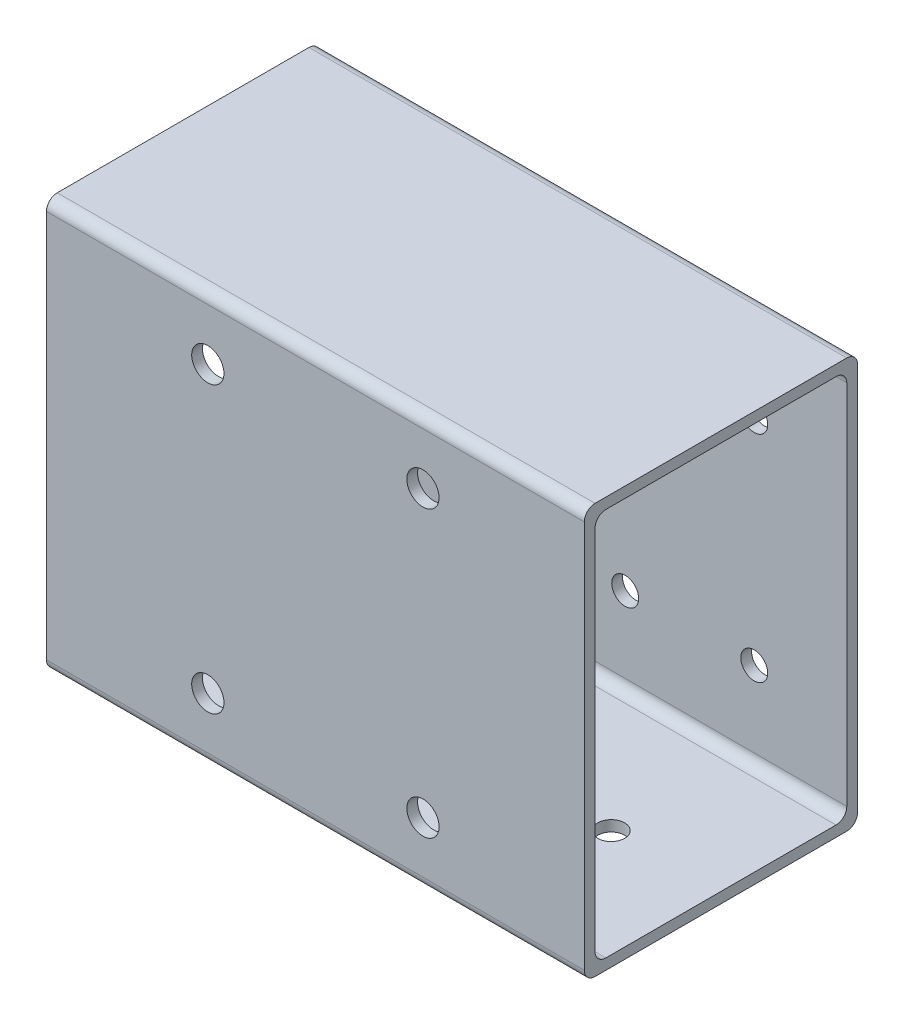
SolidWorks part; units mm, degrees
material "A500"
ref_plane "Alzado" through (0, 0, 0) normal (0, 0, 1) x (1, 0, 0)
ref_plane "Planta" through (0, 0, 0) normal (0, 1, 0) x (1, 0, 0)
ref_plane "Vista lateral" through (0, 0, 0) normal (1, 0, 0) x (0, 0, -1)
sketch "Sketch1" plane through (0, 0, 0) normal (1, 0, 0) x (0, 0, -1)
  line L1 (25.4, 38.1) -> (-25.4, 38.1)
  line L2 (25.4, 38.1) -> (25.4, -38.1)
  line L3 (25.4, -38.1) -> (-25.4, -38.1)
  line L4 (-25.4, 38.1) -> (-25.4, -38.1)
  line L5 (25.4, 38.1) -> (-25.4, -38.1) construction
  line L6 (25.4, -38.1) -> (-25.4, 38.1) construction
  point P0 (0, 0)
  dimension "D1" = 76.2
  dimension "D2" = 50.8
extrude "Boss-Extrude1" add sketch "Sketch1" against normal blind 100
sketch "Sketch2" plane through (0, 0, 0) normal (1, 0, 0) x (0, 0, -1)
  line L0 (25.4, 38.1) -> (-25.4, 38.1) construction
  line L1 (23.4, 36.1) -> (-23.4, 36.1)
  line L2 (23.4, 36.1) -> (23.4, -36.1)
  line L3 (23.4, -36.1) -> (-23.4, -36.1)
  line L4 (-23.4, 36.1) -> (-23.4, -36.1)
  line L5 (23.4, 36.1) -> (-23.4, -36.1) construction
  line L6 (23.4, -36.1) -> (-23.4, 36.1) construction
  line L7 (25.4, -38.1) -> (25.4, 38.1) construction
  point P0 (0, 0)
  dimension "D1" = 2
  dimension "D2" = 2
extrude "Cut-Extrude1" cut sketch "Sketch2" against normal through all
fillet "Fillet2" radius 2 8 edges at (-50, -38.1, -25.4) (-50, -38.1, 25.4) (-50, 38.1, 25.4) (-50, 38.1, -25.4) (-50, -36.1, -23.4) (-50, 36.1, -23.4) (-50, -36.1, 23.4) (-50, 36.1, 23.4)
sketch "Croquis2" plane through (0, 0, 25.4) normal (0, 0, 1) x (1, 0, 0)
  line L0 (-50, 36.1) -> (-50, -36.1) construction
  line L1 (0, 36.1) -> (-100, 36.1) construction
  line L2 (-100, -36.1) -> (0, -36.1) construction
  line L4 (-30, 26.5) -> (-70, 26.5)
  line L5 (-30, 26.5) -> (-30, -26.5)
  line L6 (-30, -26.5) -> (-70, -26.5)
  line L7 (-70, 26.5) -> (-70, -26.5)
  line L8 (-30, 26.5) -> (-70, -26.5) construction
  line L9 (-30, -26.5) -> (-70, 26.5) construction
  circle A0 centre (-70, 26.5) radius 3
  circle A1 centre (-30, 26.5) radius 3
  circle A2 centre (-30, -26.5) radius 3
  circle A3 centre (-70, -26.5) radius 3
  point P6 (-50, 0)
  dimension "D3" = 6
  dimension "D4" = 6
  dimension "D5" = 6
  dimension "D6" = 6
  dimension "D1" = 53
  dimension "D2" = 40
extrude "Cortar-Extruir2" cut sketch "Croquis2" against normal blind 10 contours L5 A1 L4 | L4 A1 L5 | L4 A0 L7 | L7 A0 L4 | L6 A3 L7 | L7 A3 L6 | L6 A2 L5 | L5 A2 L6
sketch "Croquis4" plane through (0, 0, -25.4) normal (0, 0, -1) x (-1, 0, 0)
  line L0 (49.2, 38.1) -> (49.2, -38.1) construction
  line L2 (0, 38.1) -> (100, 38.1) construction
  line L3 (100, -38.1) -> (0, -38.1) construction
  line L6 (100, -36.1) -> (100, 36.1) construction
  line L7 (100, 23.1) -> (49.2, 23.1) construction
  line L8 (100, -23.1) -> (49.2, -23.1) construction
  line L9 (49.2, 0) -> (100, 0) construction
  circle A1 centre (90, 23.1) radius 2.5
  circle A2 centre (59.2, 23.1) radius 2.5
  circle A3 centre (59.2, -23.1) radius 2.5
  circle A4 centre (90, -23.1) radius 2.5
  circle A5 centre (74.6, 0) radius 2.5
  dimension "D3" = 15
  dimension "D4" = 5
  dimension "D5" = 5
  dimension "D6" = 5
  dimension "D7" = 5
  dimension "D8" = 5
  dimension "D1" = 50.8
  dimension "D2" = 15
  dimension "D9" = 10
  dimension "D10" = 10
  dimension "D11" = 10
  dimension "D12" = 10
extrude "Cortar-Extruir5" cut sketch "Croquis4" against normal blind 10
sketch "Croquis6" plane through (0, 0, -25.4) normal (0, 0, -1) x (-1, 0, 0)
  line L0 (49.2, 38.1) -> (49.2, -38.1) construction
  line L8 (0, 0) -> (41.2, 0) construction
  line L9 (41.2, 20) -> (17.2, 20)
  line L10 (41.2, 20) -> (41.2, -20)
  line L11 (41.2, -20) -> (17.2, -20)
  line L12 (17.2, 20) -> (17.2, -20)
  line L13 (0, -36.1) -> (0, 36.1) construction
  line L14 (0, 38.1) -> (100, 38.1) construction
  line L15 (100, -38.1) -> (0, -38.1) construction
  line L16 (100, -36.1) -> (100, 36.1) construction
  circle A0 centre (17.2, 20) radius 2.5
  circle A1 centre (17.2, -20) radius 2.5
  circle A2 centre (41.2, -20) radius 2.5
  circle A3 centre (41.2, 20) radius 2.5
  dimension "D5" = 5
  dimension "D6" = 5
  dimension "D7" = 5
  dimension "D8" = 5
  dimension "D1" = 8
  dimension "D2" = 24
  dimension "D3" = 40
  dimension "D4" = 20
  dimension "D9" = 50.8
extrude "Cortar-Extruir6" cut sketch "Croquis6" against normal blind 10 contours A0 | A3 | A2 | A1
sketch "Croquis7" plane through (0, -38.1, 0) normal (0, -1, 0) x (1, 0, 0)
  line L0 (0, 0.4) -> (-100, 0.4) construction
  line L1 (0, 23.4) -> (0, -23.4) construction
  line L2 (-100, 23.4) -> (-100, -23.4) construction
  line L3 (-100, 25.4) -> (0, 25.4) construction
  circle A0 centre (-20, 0.4) radius 2.5
  circle A1 centre (-80, 0.4) radius 2.5
  dimension "D2" = 5
  dimension "D5" = 5
  dimension "D1" = 25
  dimension "D3" = 20
  dimension "D4" = 20
extrude "Cortar-Extruir7" cut sketch "Croquis7" against normal blind 10
